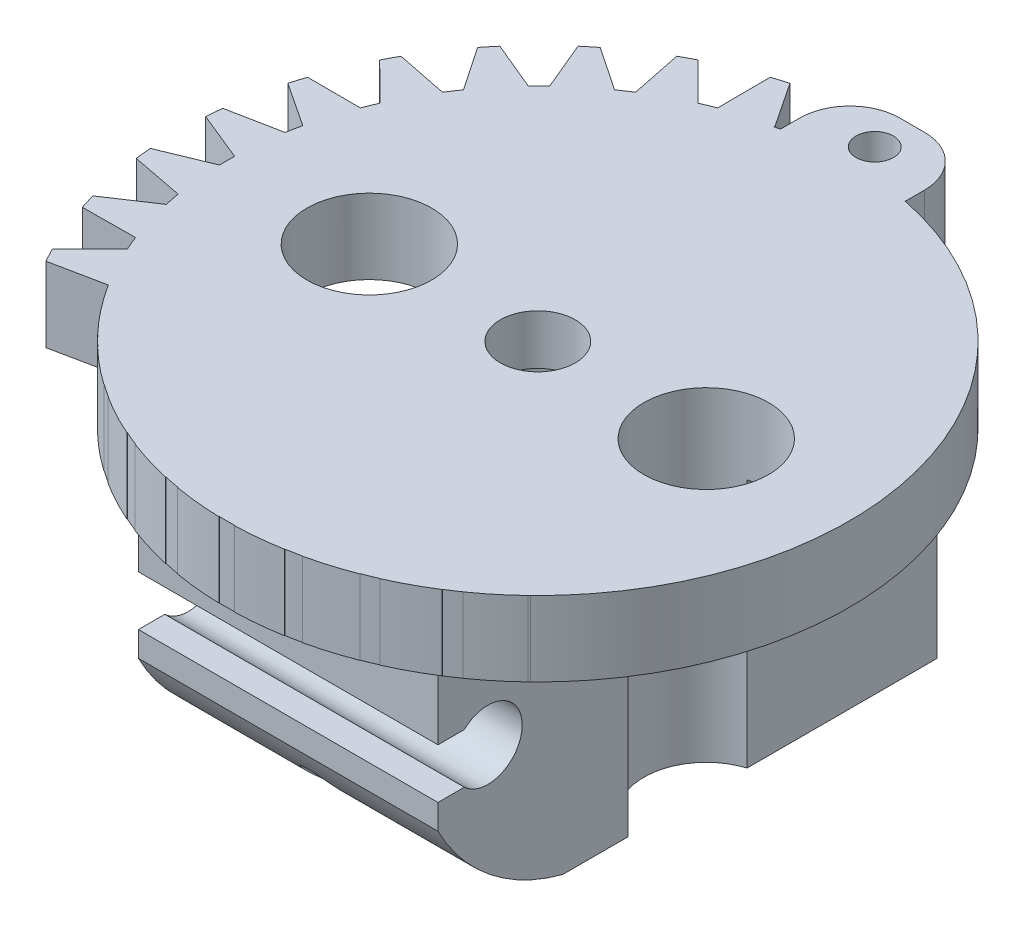
SolidWorks part; units mm, degrees
ref_plane "Front Plane" through (0, 0, 0) normal (0, 0, 1) x (1, 0, 0)
ref_plane "Top Plane" through (0, 0, 0) normal (0, 1, 0) x (1, 0, 0)
ref_plane "Right Plane" through (0, 0, 0) normal (1, 0, 0) x (0, 0, -1)
sketch "Sketch1" plane through (0, 0, 0) normal (0, 1, 0) x (1, 0, 0)
  circle A0 centre (0, 0) radius 5.5
  dimension "D1" = 11
extrude "Boss-Extrude1" add sketch "Sketch1" along normal blind 7
sketch "Sketch2" plane through (0, 7, 0) normal (0, 1, 0) x (1, 0, 0)
  circle A0 centre (0, 0) radius 3
  dimension "D1" = 6
extrude "Cut-Extrude1" cut sketch "Sketch2" against normal blind 5
sketch "Sketch3" plane through (0, 0, 0) normal (0, -1, 0) x (1, 0, 0)
  circle A0 centre (0, 0) radius 10.5
  dimension "D1" = 21
extrude "Boss-Extrude2" add sketch "Sketch3" along normal blind 3
sketch "Sketch4" plane through (0, -3, 0) normal (0, -1, 0) x (1, 0, 0)
  line L0 (2.7362, 12.158) -> (3.9105, 13.9242)
  line L3 (4.516, 13.7405) -> (4.5046, 11.6221)
  line L4 (5.0634, 11.3908) -> (6.5597, 12.8939)
  line L5 (7.1178, 12.5956) -> (6.6933, 10.5201)
  line L6 (7.1962, 10.1843) -> (8.957, 11.3666)
  line L7 (9.4462, 10.9651) -> (8.6249, 9.0124)
  line L8 (9.0527, 8.5848) -> (11.0103, 9.401)
  line L9 (11.4117, 8.9118) -> (10.2253, 7.1567)
  line L10 (0.304, 12.4565) -> (1.1112, 14.4178)
  line L11 (1.7409, 14.3558) -> (2.143, 12.2759)
  line L12 (10.5614, 6.654) -> (12.6406, 7.0725)
  line L13 (12.9389, 6.5144) -> (11.4329, 5.0245)
  line L14 (11.6645, 4.4658) -> (13.7854, 4.4707)
  line L15 (13.9691, 3.8651) -> (12.2013, 2.6977)
  line L16 (12.3195, 2.1046) -> (14.4006, 1.6956)
  line L17 (14.4626, 1.0658) -> (12.5011, 0.2657)
  line L18 (12.5012, -0.3391) -> (14.4625, -1.1462)
  line L19 (14.4005, -1.776) -> (12.3206, -2.1781)
  line L20 (12.2027, -2.7713) -> (13.9689, -3.9456)
  line L21 (13.7852, -4.5511) -> (11.6668, -4.5397)
  line L22 (11.4355, -5.0985) -> (12.9386, -6.5948)
  line L23 (12.6403, -7.1529) -> (10.5648, -6.7284)
  line L24 (10.229, -7.2313) -> (11.4113, -8.9921)
  line L25 (11.0098, -9.4813) -> (9.0571, -8.66)
  line L26 (8.6295, -9.0878) -> (9.4457, -11.0454)
  line L27 (8.9565, -11.4468) -> (7.2014, -10.2604)
  line L28 (6.6987, -10.5965) -> (7.1172, -12.6757)
  line L29 (6.5591, -12.974) -> (5.0692, -11.468)
  line L30 (4.5105, -11.6996) -> (4.5154, -13.8205)
  line L31 (3.9098, -14.0042) -> (2.7424, -12.2364)
  line L32 (2.1493, -12.3546) -> (1.7403, -14.4357)
  line L33 (1.1105, -14.4977) -> (0.3104, -12.5362)
  line L34 (-0.2944, -12.5363) -> (-1.1015, -14.4976)
  line L35 (-1.7313, -14.4356) -> (-2.1334, -12.3557)
  line L36 (-2.7266, -12.2378) -> (-3.9009, -14.004)
  line L37 (-4.5064, -13.8203) -> (-4.495, -11.7019)
  line L38 (-5.0538, -11.4706) -> (-6.5501, -12.9737)
  line L39 (-7.1082, -12.6754) -> (-6.6837, -10.5999)
  line L40 (-7.1866, -10.264) -> (-8.9474, -11.4464)
  line L41 (-9.4366, -11.0449) -> (-8.6153, -9.0922)
  line L42 (-9.0431, -8.6646) -> (-11.0007, -9.4807)
  line L43 (-11.4021, -8.9915) -> (-10.2157, -7.2365)
  line L44 (-10.5518, -6.7337) -> (-12.631, -7.1523)
  line L45 (-12.9293, -6.5942) -> (-11.4233, -5.1043)
  line L46 (-11.6549, -4.5456) -> (-13.7758, -4.5505)
  line L47 (-13.9595, -3.9449) -> (-12.1917, -2.7775)
  line L48 (-12.3099, -2.1843) -> (-14.391, -1.7754)
  line L49 (-14.453, -1.1456) -> (-12.4915, -0.3455)
  line L50 (-12.4916, 0.2593) -> (-14.4529, 1.0665)
  line L51 (-14.3909, 1.6962) -> (-12.311, 2.0983)
  line L52 (-12.1931, 2.6915) -> (-13.9593, 3.8658)
  line L53 (-13.7756, 4.4713) -> (-11.6572, 4.4599)
  line L54 (-11.4259, 5.0187) -> (-12.929, 6.515)
  line L55 (-12.6307, 7.0731) -> (-10.5552, 6.6486)
  line L56 (-10.2193, 7.1515) -> (-11.4017, 8.9123)
  line L57 (-11.0002, 9.4015) -> (-9.0475, 8.5802)
  line L58 (-8.6199, 9.008) -> (-9.436, 10.9656)
  line L59 (-8.9468, 11.367) -> (-7.1918, 10.1806)
  line L60 (-6.689, 10.5167) -> (-7.1076, 12.5959)
  line L61 (-6.5495, 12.8942) -> (-5.0596, 11.3882)
  line L62 (-4.5009, 11.6198) -> (-4.5058, 13.7407)
  line L63 (-3.9002, 13.9244) -> (-2.7328, 12.1566)
  line L64 (-2.1397, 12.2748) -> (-1.7307, 14.3559)
  line L65 (-1.1009, 14.4179) -> (-0.3008, 12.4564)
  arc A3 (1.7409, 14.3558) -> (1.1112, 14.4178) centre (0.0048, -0.0399) ccw
  arc A5 (4.516, 13.7405) -> (3.9105, 13.9242) centre (0.0048, -0.0399) ccw
  arc A7 (7.1178, 12.5956) -> (6.5597, 12.8939) centre (0.0048, -0.0399) ccw
  arc A9 (9.4462, 10.9651) -> (8.957, 11.3666) centre (0.0048, -0.0399) ccw
  arc A11 (11.4117, 8.9118) -> (11.0103, 9.401) centre (0.0048, -0.0399) ccw
  arc A13 (12.9389, 6.5144) -> (12.6406, 7.0725) centre (0.0048, -0.0399) ccw
  arc A15 (13.9691, 3.8651) -> (13.7854, 4.4707) centre (0.0048, -0.0399) ccw
  arc A17 (14.4626, 1.0658) -> (14.4006, 1.6956) centre (0.0048, -0.0399) ccw
  arc A19 (14.4005, -1.776) -> (14.4625, -1.1462) centre (0.0048, -0.0399) ccw
  arc A21 (13.7852, -4.5511) -> (13.9689, -3.9456) centre (0.0048, -0.0399) ccw
  arc A23 (12.6403, -7.1529) -> (12.9386, -6.5948) centre (0.0048, -0.0399) ccw
  arc A25 (11.0098, -9.4813) -> (11.4113, -8.9921) centre (0.0048, -0.0399) ccw
  arc A27 (8.9565, -11.4468) -> (9.4457, -11.0454) centre (0.0048, -0.0399) ccw
  arc A29 (6.5591, -12.974) -> (7.1172, -12.6757) centre (0.0048, -0.0399) ccw
  arc A31 (3.9098, -14.0042) -> (4.5154, -13.8205) centre (0.0048, -0.0399) ccw
  arc A33 (1.1105, -14.4977) -> (1.7403, -14.4357) centre (0.0048, -0.0399) ccw
  arc A35 (-1.7313, -14.4356) -> (-1.1015, -14.4976) centre (0.0048, -0.0399) ccw
  arc A37 (-4.5064, -13.8203) -> (-3.9009, -14.004) centre (0.0048, -0.0399) ccw
  arc A39 (-7.1082, -12.6754) -> (-6.5501, -12.9737) centre (0.0048, -0.0399) ccw
  arc A41 (-9.4366, -11.0449) -> (-8.9474, -11.4464) centre (0.0048, -0.0399) ccw
  arc A43 (-11.4021, -8.9915) -> (-11.0007, -9.4807) centre (0.0048, -0.0399) ccw
  arc A45 (-12.9293, -6.5942) -> (-12.631, -7.1523) centre (0.0048, -0.0399) ccw
  arc A47 (-13.9595, -3.9449) -> (-13.7758, -4.5505) centre (0.0048, -0.0399) ccw
  arc A49 (-14.453, -1.1456) -> (-14.391, -1.7754) centre (0.0048, -0.0399) ccw
  arc A51 (-14.3909, 1.6962) -> (-14.4529, 1.0665) centre (0.0048, -0.0399) ccw
  arc A53 (-13.7756, 4.4713) -> (-13.9593, 3.8658) centre (0.0048, -0.0399) ccw
  arc A55 (-12.6307, 7.0731) -> (-12.929, 6.515) centre (0.0048, -0.0399) ccw
  arc A57 (-11.0002, 9.4015) -> (-11.4017, 8.9123) centre (0.0048, -0.0399) ccw
  arc A59 (-8.9468, 11.367) -> (-9.436, 10.9656) centre (0.0048, -0.0399) ccw
  arc A61 (-6.5495, 12.8942) -> (-7.1076, 12.5959) centre (0.0048, -0.0399) ccw
  arc A63 (-3.9002, 13.9244) -> (-4.5058, 13.7407) centre (0.0048, -0.0399) ccw
  arc A65 (-1.1009, 14.4179) -> (-1.7307, 14.3559) centre (0.0048, -0.0399) ccw
  arc A67 (-4.5009, 11.6198) -> (-5.0596, 11.3882) centre (0.0048, -0.0399) ccw
  arc A70 (-2.1397, 12.2748) -> (-2.7328, 12.1566) centre (0.0048, -0.0399) ccw
  arc A71 (0.304, 12.4565) -> (-0.3008, 12.4564) centre (0.0048, -0.0399) ccw
  arc A72 (2.7362, 12.158) -> (2.143, 12.2759) centre (0.0048, -0.0399) ccw
  arc A73 (5.0634, 11.3908) -> (4.5046, 11.6221) centre (0.0048, -0.0399) ccw
  arc A74 (7.1962, 10.1843) -> (6.6933, 10.5201) centre (0.0048, -0.0399) ccw
  arc A75 (9.0527, 8.5848) -> (8.6249, 9.0124) centre (0.0048, -0.0399) ccw
  arc A76 (10.5614, 6.654) -> (10.2253, 7.1567) centre (0.0048, -0.0399) ccw
  arc A77 (11.6645, 4.4658) -> (11.4329, 5.0245) centre (0.0048, -0.0399) ccw
  arc A78 (12.3195, 2.1046) -> (12.2013, 2.6977) centre (0.0048, -0.0399) ccw
  arc A79 (12.5012, -0.3391) -> (12.5011, 0.2657) centre (0.0048, -0.0399) ccw
  arc A80 (-6.689, 10.5167) -> (-7.1918, 10.1806) centre (0.0048, -0.0399) ccw
  arc A81 (-8.6199, 9.008) -> (-9.0475, 8.5802) centre (0.0048, -0.0399) ccw
  arc A82 (-10.2193, 7.1515) -> (-10.5552, 6.6486) centre (0.0048, -0.0399) ccw
  arc A83 (-11.4259, 5.0187) -> (-11.6572, 4.4599) centre (0.0048, -0.0399) ccw
  arc A84 (-12.1931, 2.6915) -> (-12.311, 2.0983) centre (0.0048, -0.0399) ccw
  arc A85 (-12.3099, -2.1843) -> (-12.1917, -2.7775) centre (0.0048, -0.0399) ccw
  arc A86 (-11.6549, -4.5456) -> (-11.4233, -5.1043) centre (0.0048, -0.0399) ccw
  arc A87 (-9.0431, -8.6646) -> (-8.6153, -9.0922) centre (0.0048, -0.0399) ccw
  arc A88 (-7.1866, -10.264) -> (-6.6837, -10.5999) centre (0.0048, -0.0399) ccw
  arc A89 (-5.0538, -11.4706) -> (-4.495, -11.7019) centre (0.0048, -0.0399) ccw
  arc A90 (-10.5518, -6.7337) -> (-10.2157, -7.2365) centre (0.0048, -0.0399) ccw
  arc A91 (-2.7266, -12.2378) -> (-2.1334, -12.3557) centre (0.0048, -0.0399) ccw
  arc A92 (-0.2944, -12.5363) -> (0.3104, -12.5362) centre (0.0048, -0.0399) ccw
  arc A93 (2.1493, -12.3546) -> (2.7424, -12.2364) centre (0.0048, -0.0399) ccw
  arc A94 (4.5105, -11.6996) -> (5.0692, -11.468) centre (0.0048, -0.0399) ccw
  arc A95 (6.6987, -10.5965) -> (7.2014, -10.2604) centre (0.0048, -0.0399) ccw
  arc A96 (8.6295, -9.0878) -> (9.0571, -8.66) centre (0.0048, -0.0399) ccw
  arc A97 (10.229, -7.2313) -> (10.5648, -6.7284) centre (0.0048, -0.0399) ccw
  arc A98 (11.4355, -5.0985) -> (11.6668, -4.5397) centre (0.0048, -0.0399) ccw
  arc A99 (12.2027, -2.7713) -> (12.3206, -2.1781) centre (0.0048, -0.0399) ccw
  arc A100 (-12.4916, 0.2593) -> (-12.4915, -0.3455) centre (0.0048, -0.0399) ccw
  point P132 (0.0048, -0.0399)
  dimension "D1" = 32
  dimension "D2" = 14.5
  dimension "D3" = 12.5
extrude "Boss-Extrude3" add sketch "Sketch4" against normal blind 3 separate body
sketch "Sketch6" plane through (0, -3, 0) normal (0, -1, 0) x (1, 0, 0)
  line L1 (-6, 10) -> (6, 10)
  line L2 (-6, 10) -> (-6, -10)
  line L3 (-6, -10) -> (6, -10)
  line L4 (6, 10) -> (6, -10)
  line L5 (0, -11) -> (0, 11) construction
  line L6 (11, 0) -> (-11, 0) construction
  dimension "D1" = 12
  dimension "D2" = 20
  dimension "D3" = 6
  dimension "D4" = 10
extrude "Boss-Extrude4" add sketch "Sketch6" along normal blind 10
sketch "Sketch7" plane through (-6, 0, 0) normal (-1, 0, 0) x (0, 0, 1)
  line L0 (10, -13) -> (10, -3) construction
  line L1 (10, -3) -> (-10, -3) construction
  line L3 (8, -7) -> (10, -7)
  line L4 (8, -7) -> (8, -6)
  line L5 (8, -6) -> (10, -6)
  line L6 (10, -7) -> (10, -6)
  line L7 (8, -7) -> (10, -7)
  line L8 (8, -7) -> (8, -8)
  line L9 (8, -8) -> (10, -8)
  line L10 (10, -7) -> (10, -8)
  circle A0 centre (8, -7) radius 1.375
  line M9 (10, -13) -> (10, -3)
  dimension "D1" = 2
  dimension "D5" = 2.75
  dimension "D2" = 4
  dimension "D3" = 2
  dimension "D4" = 1
extrude "Cut-Extrude3" cut sketch "Sketch7" against normal through all both and the other way through all contours L5 A0 L9 L8 L4 | L9 A0 L3 L8 | L3 A0 L5 L4 | A0 L9 L7 M9 | A0 L7 L5 M9
sketch "Sketch8" plane through (-6, 0, 0) normal (-1, 0, 0) x (0, 0, 1)
  line L0 (10, -13) -> (10, -8) construction
  line L1 (10, -13) -> (-10, -13) construction
  line L2 (10, -9) -> (10, -13)
  line L3 (5, -13) -> (10, -13)
  arc A0 (10, -9) -> (5, -13) centre (3.0305, -5.4131) cw
  dimension "D1" = 1
  dimension "D2" = 5
extrude "Cut-Extrude4" cut sketch "Sketch8" against normal through all both and the other way through all
sketch "Sketch10" plane through (0, 0, -10) normal (0, 0, -1) x (-1, 0, 0)
  line L0 (0, 11) -> (0, -11) construction
  line L1 (-0.3104, -3) -> (-1.1105, -3) construction
  circle A0 centre (0, -11) radius 0.75
  dimension "D2" = 1.5
  dimension "D1" = 8
extrude "Cut-Extrude6" cut sketch "Sketch10" against normal through all both and the other way through all
sketch "Sketch12" plane through (0, -3, 0) normal (0, -1, 0) x (1, 0, 0)
  line L0 (-2.7128, -12.1761) -> (-3.3416, -14.9984)
  line L1 (-10.5552, 6.6486) -> (-12.6418, 8.7351)
  arc A1 (-3.3416, -14.9984) -> (-12.6418, 8.7351) centre (0, 0) ccw
  arc A2 (-2.7128, -12.1761) -> (-10.5552, 6.6486) centre (0, 0) ccw
extrude "Cut-Extrude9" cut sketch "Sketch12" against normal blind 10
sketch "Sketch14" plane through (0, -3, 0) normal (0, -1, 0) x (1, 0, 0)
  line L0 (11, 0) -> (-11, 0) construction
  line L1 (-2.5, 0) -> (2.5, 0)
  line L2 (-2.5, 0) -> (-2.5, -13)
  line L3 (-0.5, -15) -> (0.5, -15)
  line L4 (2.5, 0) -> (2.5, -13)
  line L5 (0, -11) -> (0, 11) construction
  arc A0 (0.5, -15) -> (2.5, -13) centre (0.5, -13) ccw
  arc A1 (-0.5, -15) -> (-2.5, -13) centre (-0.5, -13) cw
  circle A2 centre (0, -13.5) radius 0.75
  dimension "D4" = 2
  dimension "D5" = 1.5
  dimension "D6" = 1.5
  dimension "D1" = 5
  dimension "D2" = 2.5
  dimension "D3" = 15
extrude "Boss-Extrude5" add sketch "Sketch14" against normal up to surface (3 mm away) up to face at (0, 0, 5.5)
sketch "Sketch5" plane through (0, -3, 0) normal (0, -1, 0) x (1, 0, 0)
  circle A0 centre (0, 0) radius 3
  dimension "D1" = 6
extrude "Cut-Extrude2" cut sketch "Sketch5" against normal through all both and the other way through all
sketch "Sketch17" plane through (0, 7, 0) normal (0, 1, 0) x (1, 0, 0)
  circle A0 centre (0, 0) radius 5.5
extrude "Cut-Extrude10" cut sketch "Sketch17" against normal up to surface (7 mm away) up to face at (0, 0, 5.5)
sketch "Sketch18" plane through (0, 0, 0) normal (0, 1, 0) x (1, 0, 0)
  circle A0 centre (0, 0) radius 5.143
  circle A1 centre (0, 0) radius 1.5
  dimension "D1" = 3
extrude "Boss-Extrude6" add sketch "Sketch18" against normal blind 2
sketch "Sketch19" plane through (0, 0, 0) normal (0, 1, 0) x (1, 0, 0)
  line L0 (-7.15, 0) -> (7.15, 0) construction
  line L1 (0, -7.15) -> (0, 7.15) construction
  circle A0 centre (-6.75, 0) radius 2.5
  circle A1 centre (6.75, 0) radius 2.5
  dimension "D1" = 5
  dimension "D2" = 5
  dimension "D3" = 13.5
  dimension "D4" = 6.75
extrude "Cut-Extrude11" cut sketch "Sketch19" against normal through all
